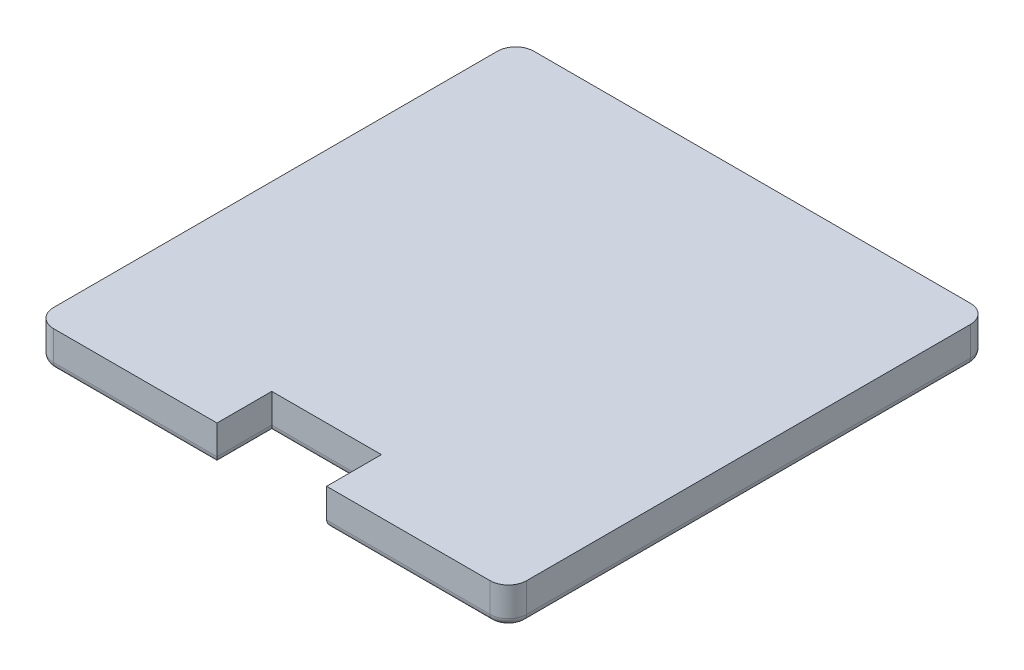
SolidWorks part; units mm, degrees
ref_plane "Front Plane" through (0, 0, 0) normal (0, 0, 1) x (1, 0, 0)
ref_plane "Top Plane" through (0, 0, 0) normal (0, 1, 0) x (1, 0, 0)
ref_plane "Right Plane" through (0, 0, 0) normal (1, 0, 0) x (0, 0, -1)
sketch "Sketch1" plane through (0, 0, 0) normal (0, 1, 0) x (1, 0, 0)
  line L0 (-3.81, -16.7005) -> (-3.81, -12.8905)
  line L1 (-15.1765, -16.7005) -> (-3.81, -16.7005)
  line L2 (-16.4465, -15.4305) -> (-16.4465, 15.4305)
  line L3 (-15.1765, 16.7005) -> (15.1765, 16.7005)
  line L4 (16.4465, -15.4305) -> (16.4465, 15.4305)
  line L5 (-16.4465, -16.7005) -> (16.4465, 16.7005) construction
  line L6 (-16.4465, 16.7005) -> (16.4465, -16.7005) construction
  line L7 (-3.81, -12.8905) -> (3.81, -12.8905)
  line L8 (3.81, -12.8905) -> (3.81, -16.7005)
  line L9 (3.81, -16.7005) -> (15.1765, -16.7005)
  arc A0 (-15.1765, -16.7005) -> (-16.4465, -15.4305) centre (-15.1765, -15.4305) cw
  arc A1 (15.1765, -16.7005) -> (16.4465, -15.4305) centre (15.1765, -15.4305) ccw
  arc A2 (15.1765, 16.7005) -> (16.4465, 15.4305) centre (15.1765, 15.4305) cw
  arc A3 (-16.4465, 15.4305) -> (-15.1765, 16.7005) centre (-15.1765, 15.4305) cw
  point P0 (0, 0)
  point P22 (0, -12.8905)
  dimension "D3" = 1.27
  dimension "D1" = 32.893
  dimension "D2" = 33.401
  dimension "D4" = 7.62
  dimension "D5" = 3.81
extrude "Boss-Extrude1" add sketch "Sketch1" along normal blind 2.54
fillet "Fillet1" radius 0.508 12 edges at (-9.4932, 0, 16.7005) (16.0745, 0, 16.3285) (16.4465, 0, 0) (16.0745, 0, -16.3285) (0, 0, -16.7005) (-16.0745, 0, -16.3285) (-16.4465, 0, 0) (-16.0745, 0, 16.3285) (-3.81, 0, 14.7955) (0, 0, 12.8905) (3.81, 0, 14.7955) (9.4932, 0, 16.7005)
